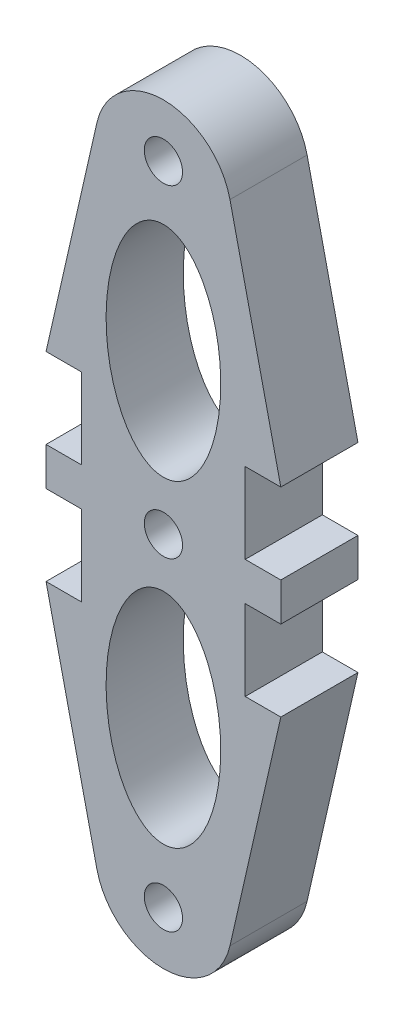
SolidWorks part; units mm, degrees
material "Acrylic (Medium-high impact)"
ref_plane "Front Plane" through (0, 0, 0) normal (0, 0, 1) x (1, 0, 0)
ref_plane "Top Plane" through (0, 0, 0) normal (0, 1, 0) x (1, 0, 0)
ref_plane "Right Plane" through (0, 0, 0) normal (1, 0, 0) x (0, 0, -1)
sketch "Sketch1" plane through (0, 0, 0) normal (0, 0, 1) x (1, 0, 0)
  line L0 (-213.0415, 464.8524) -> (49786.9585, 464.8524) construction
  line L1 (781.4592, 464.8524) -> (778.7592, 464.8524)
  line L2 (781.4592, 464.8524) -> (781.4592, 470.9524)
  line L3 (781.4592, 470.9524) -> (778.7592, 470.9524)
  line L4 (787.6592, -515.9255) -> (787.6592, 49484.0745) construction
  line L5 (-215.2215, 463.4024) -> (49784.7785, 463.4024) construction
  line L6 (793.8592, 470.9524) -> (793.8592, 487.9024) construction
  line L7 (-217.5077, 461.9524) -> (49782.4923, 461.9524) construction
  line L8 (786.2092, -537.0976) -> (786.2092, 49462.9024) construction
  line L9 (789.1092, -536.5976) -> (789.1092, 49463.4024) construction
  line L10 (793.8592, 464.8524) -> (796.5592, 464.8524)
  line L11 (781.4592, 470.9524) -> (793.8592, 470.9524) construction
  line L12 (793.8592, 470.9524) -> (796.5592, 470.9524)
  line L13 (793.8592, 464.8524) -> (793.8592, 470.9524)
  line L14 (778.7592, 464.8524) -> (778.7592, 461.9524)
  line L15 (796.5592, 464.8524) -> (796.5592, 461.9524)
  line L16 (786.2092, 487.9024) -> (782.614, 487.9024) construction
  line L17 (781.4592, 461.9524) -> (778.7592, 461.9524)
  line L18 (793.8592, 470.9524) -> (793.1379, 470.9192) construction
  line L19 (781.4592, 455.8524) -> (778.7592, 455.8524)
  line L20 (781.4592, 461.9524) -> (781.4592, 455.8524)
  line L21 (793.8592, 461.9524) -> (796.5592, 461.9524)
  line L22 (793.8592, 461.9524) -> (793.8592, 455.8524)
  line L23 (793.8592, 455.8524) -> (796.5592, 455.8524)
  line L24 (778.7592, 470.9524) -> (782.614, 487.9024)
  line L25 (792.7043, 487.9024) -> (796.5592, 470.9524)
  line L26 (792.7043, 438.9024) -> (796.5592, 455.8524)
  line L27 (789.1092, 438.9024) -> (792.7043, 438.9024) construction
  line L28 (786.2092, 438.9024) -> (782.614, 438.9024) construction
  line L29 (778.7592, 455.8524) -> (782.614, 438.9024)
  line L35 (789.1092, 487.9024) -> (792.7043, 487.9024) construction
  arc A0 (782.614, 487.9024) -> (792.7043, 487.9024) centre (787.6592, 486.755) cw
  arc A1 (782.614, 438.9024) -> (792.7043, 438.9024) centre (787.6592, 440.0498) ccw
  circle A3 centre (787.6592, 487.9024) radius 1.45
  circle A5 centre (787.6592, 438.9024) radius 1.45
  circle A6 centre (787.6592, 463.4024) radius 1.45
  ellipse E0 centre (787.6592, 475.4481) end of major axis (787.6592, 483.7502) minor radius 4.3465
  ellipse E1 centre (787.6592, 451.3566) end of major axis (787.6592, 443.0545) minor radius 4.3465
  point P10 (778.7592, 463.4024)
  point P19 (796.5592, 463.4024)
  dimension "D1" = 2.9
  dimension "D3" = 6.1
  dimension "D10" = 5.174
  dimension "D2" = 2.7
  dimension "D5" = 12.4
  dimension "D6" = 16.6042
  dimension "D7" = 8.693
  dimension "D8" = 2.2937
extrude "Boss-Extrude1" add sketch "Sketch1" along normal blind 5.85
